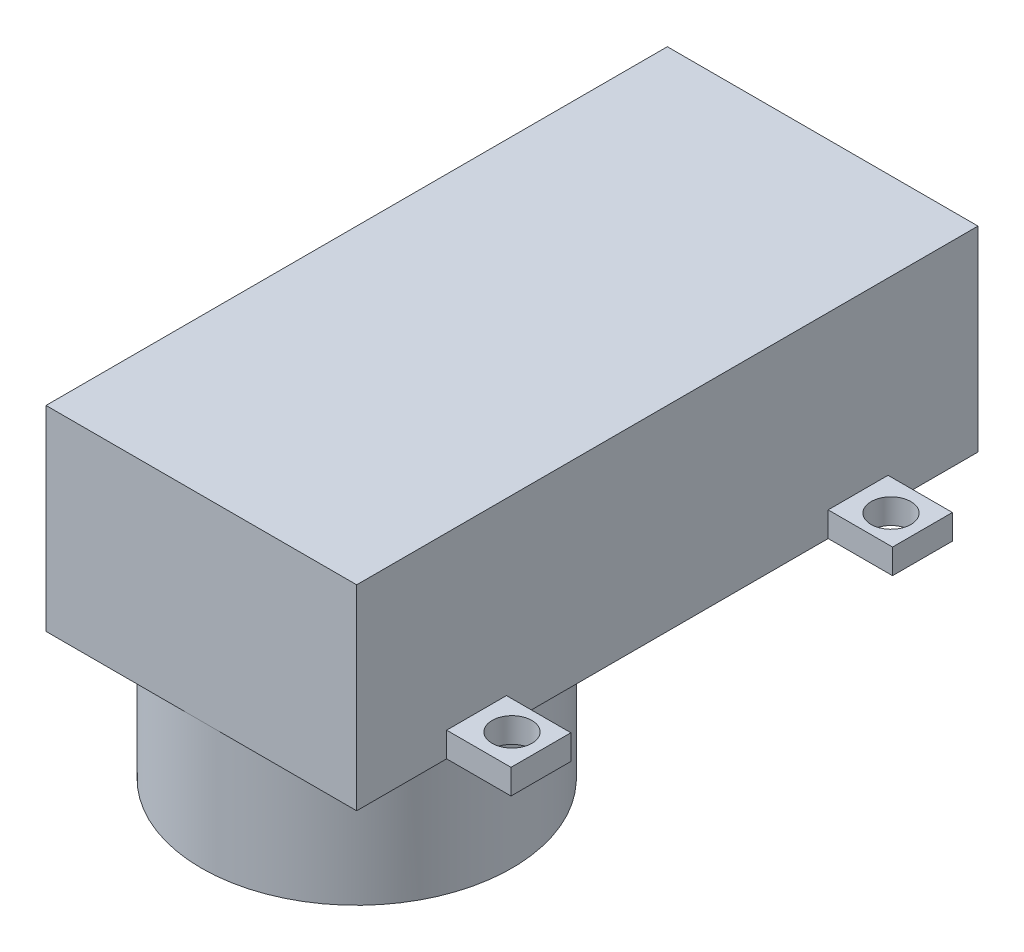
SolidWorks part; units mm, degrees
ref_plane "前视基准面" through (0, 0, 0) normal (0, 0, 1) x (1, 0, 0)
ref_plane "上视基准面" through (0, 0, 0) normal (0, 1, 0) x (1, 0, 0)
ref_plane "右视基准面" through (0, 0, 0) normal (1, 0, 0) x (0, 0, -1)
sketch "草图1" plane through (0, 0, 0) normal (0, 1, 0) x (1, 0, 0)
  line L0 (-12.5, -15.25) -> (22.3533, -15.25) construction
  line L1 (-12.5, 25) -> (12.5, 25)
  line L2 (-12.5, 25) -> (-12.5, 17.7601)
  line L3 (-12.5, -25) -> (12.5, -25)
  line L4 (12.5, 25) -> (12.5, 17.7601)
  line L5 (-12.5, 25) -> (12.5, -25) construction
  line L6 (-12.5, -25) -> (12.5, 25) construction
  line L7 (-26.8183, 0) -> (26.8183, 0) construction
  line L8 (-12.5, 15.25) -> (22.3533, 15.25) construction
  line L9 (0, 0) -> (0, 32.112) construction
  line L10 (-12.5, 12.9435) -> (-17.6802, 12.9435)
  line L11 (12.5, 17.7601) -> (17.6802, 17.7601)
  line L13 (12.5, 12.9435) -> (17.6802, 12.9435)
  line L14 (17.6802, 17.7601) -> (17.6802, 12.9435)
  line L15 (-17.6802, 17.7601) -> (-17.6802, 12.9435)
  line L16 (-12.5, 17.7601) -> (-17.6802, 17.7601)
  line L18 (12.5, -12.9435) -> (17.6802, -12.9435)
  line L19 (17.6802, -17.7601) -> (17.6802, -12.9435)
  line L20 (12.5, -17.7601) -> (17.6802, -17.7601)
  line L23 (-12.5, -17.7601) -> (-17.6802, -17.7601)
  line L24 (-17.6802, -17.7601) -> (-17.6802, -12.9435)
  line L25 (-12.5, -12.9435) -> (-17.6802, -12.9435)
  line L26 (-12.5, 12.9435) -> (-12.5, -12.9435)
  line L27 (12.5, 12.9435) -> (12.5, -12.9435)
  line L28 (-12.5, -17.7601) -> (-12.5, -25)
  line L29 (12.5, -17.7601) -> (12.5, -25)
  circle A0 centre (15.25, 15.25) radius 1.6
  circle A1 centre (-15.25, 15.25) radius 1.6
  circle A2 centre (15.25, -15.25) radius 1.6
  circle A3 centre (-15.25, -15.25) radius 1.6
  point P0 (0, 0)
  point P11 (0, 0)
  point P21 (17.6995, 12.7893)
  dimension "D4" = 3.2
  dimension "D1" = 25
  dimension "D2" = 50
  dimension "D3" = 9.75
  dimension "D5" = 15.25
extrude "凸台-拉伸1" add sketch "草图1" along normal blind 2
sketch "草图2" plane through (0, 2, 0) normal (0, 1, 0) x (1, 0, 0)
  line L0 (12.5, -25) -> (12.5, -17.7601) construction
  line L1 (-12.5, 25) -> (12.5, 25)
  line L2 (-12.5, 25) -> (-12.5, -25)
  line L3 (-12.5, -25) -> (12.5, -25)
  line L4 (12.5, 25) -> (12.5, -25)
  line L5 (-12.5, 25) -> (12.5, -25) construction
  line L6 (-12.5, -25) -> (12.5, 25) construction
  point P0 (0, 0)
extrude "凸台-拉伸2" add sketch "草图2" along normal blind 13.75
sketch "草图3" plane through (0, 0, 0) normal (0, -1, 0) x (1, 0, 0)
  line L0 (-22.4798, 0) -> (22.4798, 0) construction
  line L1 (-12.5, 25) -> (12.5, 25)
  line L2 (-12.5, 25) -> (-12.5, -25)
  line L3 (-12.5, -25) -> (12.5, -25)
  line L4 (12.5, 25) -> (12.5, -25)
  line L5 (-12.5, 25) -> (12.5, -25) construction
  line L6 (-12.5, -25) -> (12.5, 25) construction
  line L7 (0, 29.5534) -> (0, -29.5534) construction
  circle A0 centre (0, 12.5) radius 12.5
  point P0 (0, 0)
  point P10 (0, 0)
  point P13 (0, 0)
  dimension "D1" = 25
  dimension "D2" = 12.5
extrude "凸台-拉伸3" add sketch "草图3" along normal blind 10.25 contours A0
